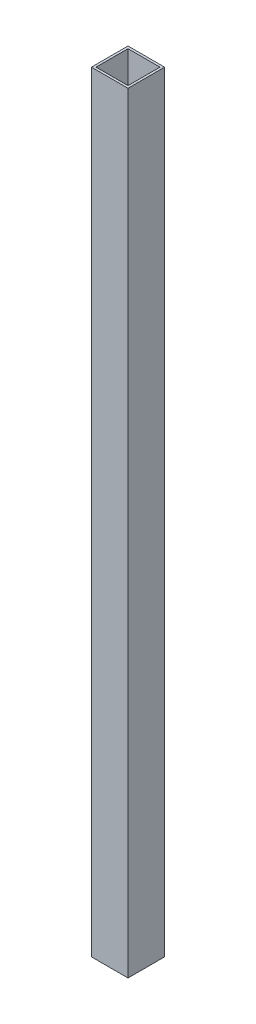
SolidWorks part; units mm, degrees
ref_plane "Front Plane" through (0, 0, 0) normal (0, 0, 1) x (1, 0, 0)
ref_plane "Top Plane" through (0, 0, 0) normal (0, 1, 0) x (1, 0, 0)
ref_plane "Right Plane" through (0, 0, 0) normal (1, 0, 0) x (0, 0, -1)
sketch "Sketch1" plane through (0, 0, 0) normal (0, 1, 0) x (1, 0, 0)
  line L0 (1.2, -1.2) -> (17.8, -1.2)
  line L1 (0, 0) -> (19, 0)
  line L2 (0, 0) -> (0, -19)
  line L3 (0, -19) -> (19, -19)
  line L4 (19, 0) -> (19, -19)
  line L5 (17.8, -1.2) -> (17.8, -17.8)
  line L6 (1.2, -17.8) -> (17.8, -17.8)
  line L7 (1.2, -1.2) -> (1.2, -17.8)
  dimension "D1" = 19
  dimension "D2" = 1.2
extrude "Boss-Extrude1" add sketch "Sketch1" along normal blind 400
